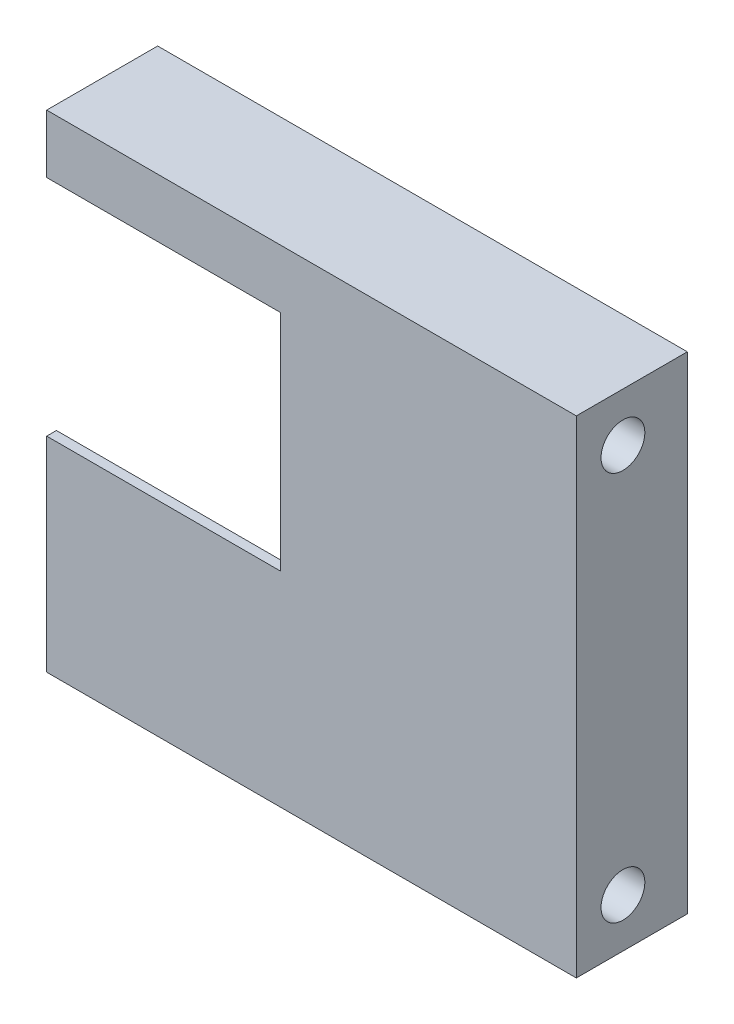
SolidWorks part; units mm, degrees
ref_plane "Front Plane" through (0, 0, 0) normal (1, 0, 0) x (0, 1, 0)
ref_plane "Top Plane" through (0, 0, 0) normal (0, 0, 1) x (0, 1, 0)
ref_plane "Right Plane" through (0, 0, 0) normal (0, 1, 0) x (-1, 0, 0)
sketch "Sketch1" plane through (0, 0, 0) normal (0, 0, 1) x (0, 1, 0)
  line L0 (-4, 25) -> (-4, 1)
  line L1 (-25, 25) -> (-4, 25)
  line L2 (-25, 25) -> (-25, -25)
  line L3 (-25, -25) -> (25, -25)
  line L4 (25, 25) -> (25, -25)
  line L5 (-25, 25) -> (25, -25) construction
  line L6 (-25, -25) -> (25, 25) construction
  line L7 (-4, 1) -> (19, 1)
  line L8 (19, 1) -> (19, 25)
  line L9 (19, 25) -> (25, 25)
  point P0 (0, 0)
  dimension "D1" = 50
  dimension "D2" = 50
  dimension "D3" = 24
  dimension "D4" = 23
extrude "Boss-Extrude1" add sketch "Sketch1" along normal blind 1
sketch "Sketch2" plane through (25, 0, 0) normal (1, 0, 0) x (0, 1, 0)
  line L1 (25, 1) -> (-25, 1)
  line L2 (25, 1) -> (25, -10.4)
  line L3 (25, -10.4) -> (-25, -10.4)
  line L4 (-25, 1) -> (-25, -10.4)
  dimension "D1" = 11.4
extrude "Boss-Extrude2" add sketch "Sketch2" along normal blind 4.4
sketch "Sketch3" plane through (29.4, 0, 0) normal (1, 0, 0) x (0, 1, 0)
  line L0 (-20, -3.7871) -> (20, -3.7871) construction
  line L1 (-25, 1) -> (-25, -10.4) construction
  circle A0 centre (-20, -3.7871) radius 2.25
  circle A1 centre (20, -3.7871) radius 2.25
  dimension "D1" = 4.5
  dimension "D2" = 4.5
  dimension "D3" = 40
  dimension "D4" = 5
extrude "Cut-Extrude1" cut sketch "Sketch3" against normal blind 4.4
sketch "Sketch4" plane through (0, 0, 0) normal (0, 0, -1) x (1, 0, 0)
  line L0 (-25, -19.5) -> (-25, -25)
  line L1 (-25, 19.5) -> (25, 19.5)
  line L3 (-25, -19.5) -> (25, -19.5)
  line L7 (-25, 25) -> (25, 25)
  line L8 (-25, 25) -> (-25, 19.5)
  line L9 (-25, -25) -> (25, -25)
  line L10 (25, 25) -> (25, 19.5)
  line L11 (-25, 25) -> (-19.5, 19.5) construction
  line L12 (-25, -25) -> (-19.5, -19.5) construction
  line L13 (19.5, 19.5) -> (25, 25) construction
  line L14 (19.5, -19.5) -> (25, -25) construction
  line L15 (25, -19.5) -> (25, -25)
  point P0 (0, 0)
  point P6 (0, 0)
  dimension "D1" = 50
  dimension "D2" = 39
extrude "Boss-Extrude3" add sketch "Sketch4" along normal blind 6.4
sketch "Sketch5" plane through (0, 0, -6.4) normal (0, 0, -1) x (1, 0, 0)
  line L0 (-25, -19.5) -> (-25, -25) construction
  line L1 (25, 20.5) -> (-25, 20.5)
  line L3 (25, -20.5) -> (-25, -20.5)
  line L5 (25, 20.5) -> (-25, -20.5) construction
  line L6 (25, -20.5) -> (-25, 20.5) construction
  line L7 (-25, -20.5) -> (-25, -25)
  line L8 (-25, 25) -> (25, 25)
  line L9 (-25, 25) -> (-25, 20.5)
  line L10 (-25, -25) -> (25, -25)
  line L11 (25, 25) -> (25, 20.5)
  line L12 (-25, 25) -> (25, -25) construction
  line L13 (-25, -25) -> (25, 25) construction
  line L14 (25, -20.5) -> (25, -25)
  point P0 (0, 0)
  point P8 (0, 0)
  dimension "D1" = 41
extrude "Boss-Extrude4" add sketch "Sketch5" along normal blind 2
sketch "Sketch6" plane through (0, 0, -8.4) normal (0, 0, -1) x (1, 0, 0)
  line L0 (-25, -20.5) -> (-25, -25) construction
  line L1 (25, 19.5) -> (-25, 19.5)
  line L3 (25, -19.5) -> (-25, -19.5)
  line L5 (25, 19.5) -> (-25, -19.5) construction
  line L6 (25, -19.5) -> (-25, 19.5) construction
  line L7 (-25, 19.5) -> (-25, 25)
  line L8 (25, -25) -> (-25, -25)
  line L9 (25, -25) -> (25, -19.5)
  line L10 (25, 25) -> (-25, 25)
  line L11 (-25, -25) -> (-25, -19.5)
  line L12 (25, -25) -> (-25, 25) construction
  line L13 (25, 25) -> (-25, -25) construction
  line L14 (25, 19.5) -> (25, 25)
  point P0 (0, 0)
  point P8 (0, 0)
  dimension "D1" = 39
extrude "Boss-Extrude5" add sketch "Sketch6" along normal blind 2
